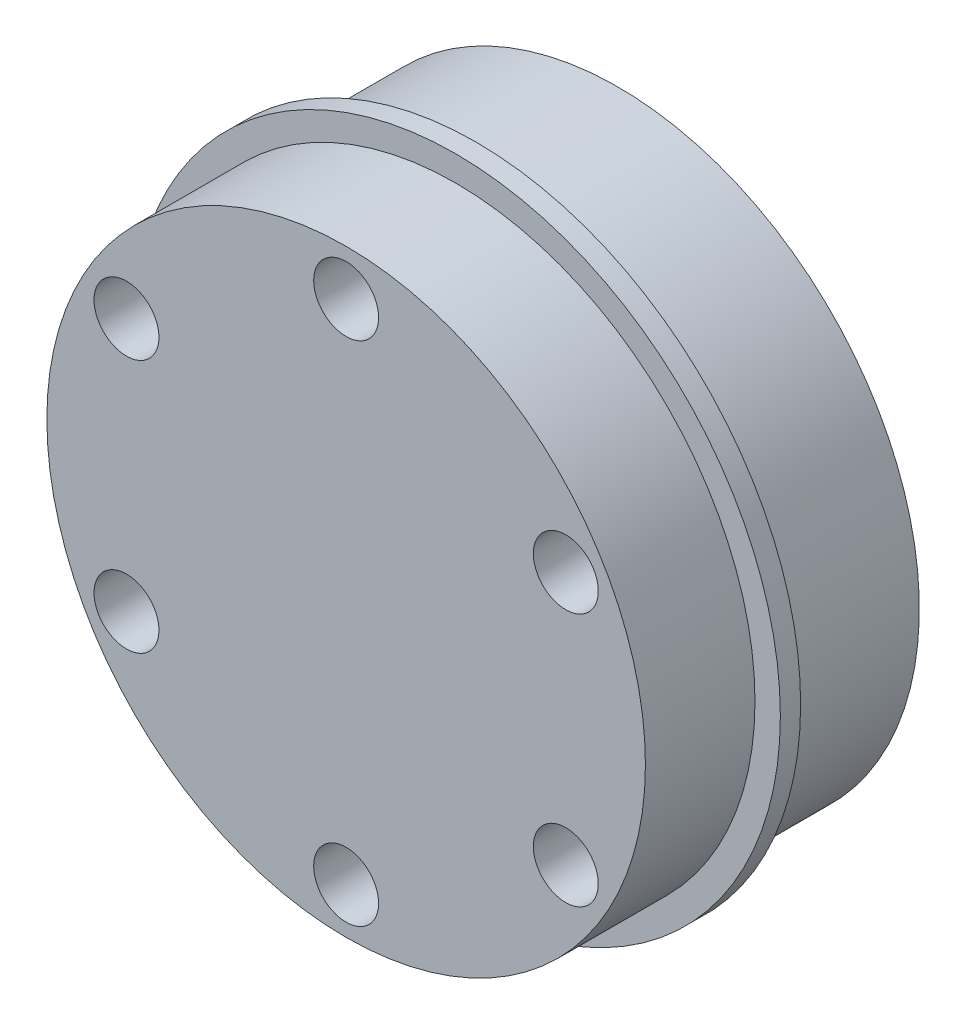
SolidWorks part; units mm, degrees
material "ABS"
ref_plane "前视基准面" through (0, 0, 0) normal (0, 0, 1) x (1, 0, 0)
ref_plane "上视基准面" through (0, 0, 0) normal (0, 1, 0) x (1, 0, 0)
ref_plane "右视基准面" through (0, 0, 0) normal (1, 0, 0) x (0, 0, -1)
other "Configuration Table"
sketch "草图1" plane through (0, 0, 0) normal (0, 0, 1) x (1, 0, 0)
  circle A0 centre (0, 0) radius 6 construction
  circle A1 centre (0, 0) radius 12.5 construction
  circle A2 centre (0, 6) radius 2.1 construction
  circle A3 centre (0, 12.5) radius 1.6 construction
  circle A4 centre (10.8253, 6.25) radius 1.6 construction
  circle A5 centre (10.8253, -6.25) radius 1.6 construction
  circle A6 centre (0, -12.5) radius 1.6 construction
  circle A7 centre (-10.8253, -6.25) radius 1.6 construction
  circle A8 centre (-10.8253, 6.25) radius 1.6 construction
  circle A9 centre (6, 0) radius 2.1 construction
  circle A10 centre (0, -6) radius 2.1 construction
  circle A11 centre (-6, 0) radius 2.1 construction
  circle A12 centre (0, 0) radius 14.75
  dimension "D1" = 12
  dimension "D2" = 25
  dimension "D3" = 4.2
  dimension "D4" = 3.2
  dimension "D7" = 29.5
  dimension "D5" = 6
  dimension "D6" = 4
extrude "凸台-拉伸1" add sketch "草图1" along normal blind 5.4
sketch "草图3" plane through (0, 0, 0) normal (0, 0, -1) x (-1, 0, 0)
  circle A0 centre (0, 0) radius 16
  dimension "D1" = 32
extrude "凸台-拉伸2" add sketch "草图3" along normal blind 1
sketch "草图4" plane through (0, 0, -1) normal (0, 0, -1) x (-1, 0, 0)
  circle A0 centre (0, 0) radius 14.85
  dimension "D1" = 29.7
extrude "凸台-拉伸3" add sketch "草图4" along normal blind 7
sketch "草图2" plane through (0, 0, 5.4) normal (0, 0, -1) x (-1, 0, 0)
  circle A0 centre (10.8253, -6.25) radius 1.6 construction
  circle A3 centre (10.8253, -6.25) radius 1.6
  circle A4 centre (10.8253, 6.25) radius 1.6 construction
  circle A5 centre (-10.8253, 6.25) radius 1.6 construction
  circle A6 centre (-10.8253, -6.25) radius 1.6 construction
  circle A7 centre (0, -12.5) radius 1.6 construction
  circle A8 centre (0, 12.5) radius 1.6 construction
  circle A9 centre (-10.8253, 6.25) radius 1.6
  circle A10 centre (-10.8253, -6.25) radius 1.6
  circle A11 centre (0, -12.5) radius 1.6
  circle A12 centre (10.8253, 6.25) radius 1.6
  circle A13 centre (0, 12.5) radius 1.6
extrude "切除-拉伸2" cut sketch "草图2" along normal through all
